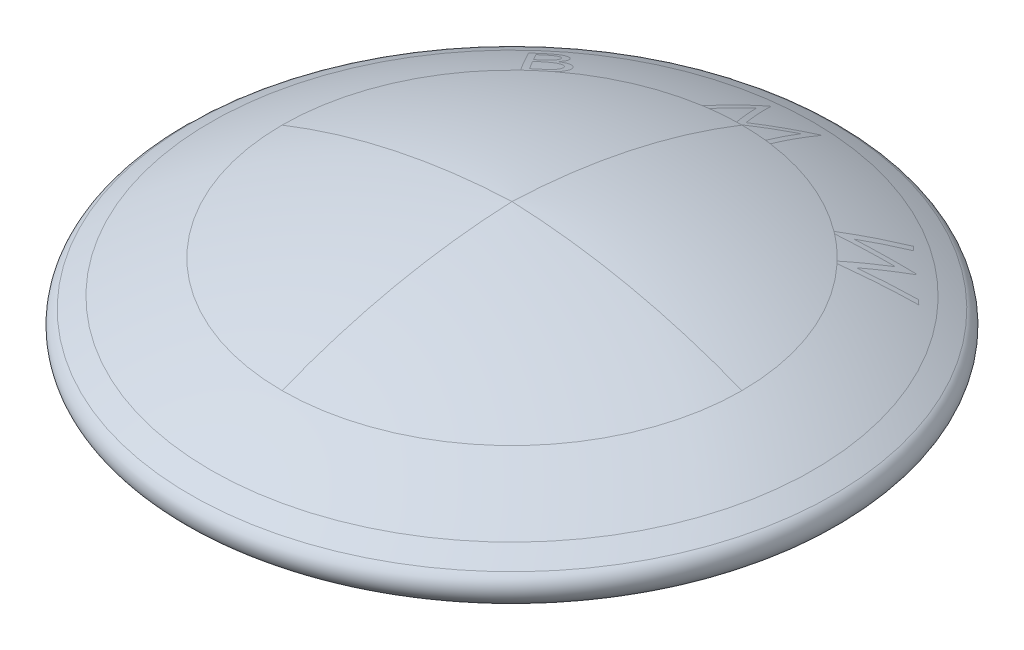
SolidWorks part; units mm, degrees
ref_plane "Front Plane" through (0, 0, 0) normal (0, 0, 1) x (1, 0, 0)
ref_plane "Top Plane" through (0, 0, 0) normal (0, 1, 0) x (1, 0, 0)
ref_plane "Right Plane" through (0, 0, 0) normal (1, 0, 0) x (0, 0, -1)
sketch "Sketch1" plane through (0, 0, 0) normal (1, 0, 0) x (0, 0, -1)
  line L0 (0, -28.1895) -> (0, 1379.2205) construction
  line L1 (0, 0) -> (5.0236, 0)
  line L2 (0, 0) -> (0, 1.9665)
  arc A0 (0, 1.9665) -> (5.1508, 0.4739) centre (-0.4444, -9.2007) cw
  arc A1 (5.0236, 0) -> (5.1508, 0.4739) centre (5.0236, 0.254) ccw
  point P6 (0, 1.9665)
  point P10 (5.8999, 0)
  dimension "D3" = 11.176
  dimension "D4" = 0.254
  dimension "D1" = 11.7998
  dimension "D2" = 1.9665
revolve "Revolve1" add sketch "Sketch1" angle 360 about L0
ref_plane "Plane1" through (0, 2.54, 0) normal (0, 1, 0) x (1, 0, 0)
sketch "Sketch2" plane through (0, 2.54, 0) normal (0, 1, 0) x (1, 0, 0)
  line L0 (0, 3.683) -> (0, -3.683)
  line L1 (3.683, 0) -> (-3.683, 0)
  circle A0 centre (0, 0) radius 4.826
  circle A1 centre (0, 0) radius 3.683
  dimension "D1" = 9.652
  dimension "D2" = 7.366
split line "Split Line2"
sketch "Sketch3" plane through (0, 2.54, 0) normal (0, 1, 0) x (1, 0, 0)
  arc A0 (-3.683, 0) -> (3.683, 0) centre (0, 0) cw construction
  arc A1 (3.683, 0) -> (0, 3.683) centre (0, 0) ccw construction
  arc A2 (0, 3.683) -> (-3.683, 0) centre (0, 0) ccw construction
  text T0 " B    M    W" font "Century Gothic" height 0.9652
  point P12 (-1.8415, 0)
  point P13 (0, 0)
  point P14 (0, 0)
  point P16 (-1.775, 0.4904)
  point P17 (0, 0)
split line "Split Line3"
